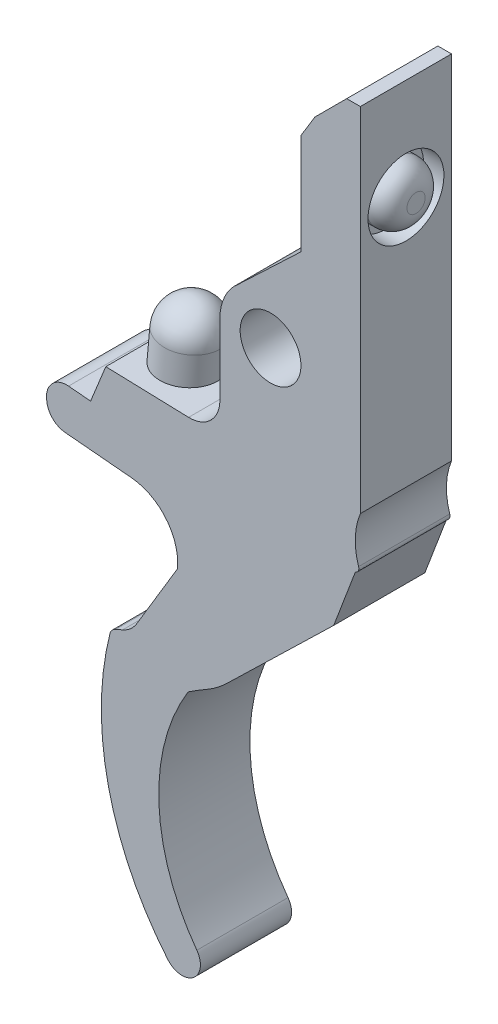
SolidWorks part; units mm, degrees
ref_plane "정면" through (0, 0, 0) normal (0, 0, 1) x (1, 0, 0)
ref_plane "윗면" through (0, 0, 0) normal (0, 1, 0) x (1, 0, 0)
ref_plane "우측면" through (0, 0, 0) normal (1, 0, 0) x (0, 0, -1)
sketch "스케치1" plane through (0, 0, 0) normal (0, 0, 1) x (1, 0, 0)
  line L0 (7.5189, 25.0781) -> (8.8664, 25.0781)
  line L1 (7.5189, 25.0781) -> (4.3842, 21.9434)
  line L2 (8.8664, 25.0781) -> (8.8664, -9.7282)
  line L3 (-5, 0) -> (-5, -10.0714)
  line L4 (-17.7666, -13.4266) -> (-19.9405, -13.2288)
  line L5 (2.9878, 19.65) -> (2.9878, 17.6612)
  line L6 (-20.2877, -17.3633) -> (-13.717, -17.9611)
  line L7 (2.9878, 17.6612) -> (2.9878, 9.7088)
  line L8 (2.9878, 9.7088) -> (-3.1847, 3.8546)
  line L9 (8.3701, -14.9782) -> (6.2381, -20.6005)
  line L10 (2.2148, 21.9434) -> (17.8049, 21.9434) construction
  line L11 (4.3842, 21.9434) -> (2.9878, 19.65)
  line L12 (6.2381, -20.6005) -> (-4.3386, -30.8592)
  line L13 (-5, -10.0714) -> (-16.2648, -9.7282)
  line L14 (-16.2648, -9.7282) -> (-17.7666, -13.4266)
  line L16 (-9.201, -23.497) -> (-13.2181, -30.1935)
  line L18 (-15.296, -31.7023) -> (-14.6082, -31.4073)
  circle A0 centre (0, 0) radius 3
  circle A1 centre (0, 0) radius 5
  arc A2 (-6.3376, -32.3623) -> (-4.3386, -30.8592) centre (-11.3009, -23.681) ccw
  arc A3 (-6.3376, -32.3623) -> (-8.1336, -33.4719) centre (9.0543, -59.2837) ccw
  arc A4 (-15.296, -31.7023) -> (-15.8352, -32.2622) centre (-14.9019, -32.6214) ccw
  arc A5 (-22.1027, -15.4958) -> (-20.2877, -17.3633) centre (-20.1065, -15.3716) ccw
  arc A6 (-19.9405, -13.2288) -> (-22.1027, -15.4958) centre (-20.1217, -15.2206) ccw
  arc A7 (8.8664, -9.7282) -> (8.6919, -14.3466) centre (15.0215, -12.2733) ccw
  arc A8 (8.6919, -14.3466) -> (8.3701, -14.9782) centre (8.2168, -14.5023) cw
  arc A9 (-13.717, -17.9611) -> (-9.201, -23.497) centre (-14.17, -22.9405) cw
  arc A11 (-14.6515, -60.0853) -> (-14.6251, -60.1395) centre (16.7757, -44.8116) ccw
  arc A13 (-8.1336, -33.4719) -> (-7.2761, -55.1306) centre (8.3107, -43.6672) ccw
  arc A14 (-15.8352, -32.2622) -> (-10.1333, -57.3697) centre (11.6079, -39.2311) ccw
  arc A15 (-10.1333, -57.3697) -> (-7.2761, -55.1306) centre (-8.7389, -56.2065) ccw
  arc A16 (-14.6082, -31.4073) -> (-13.2181, -30.1935) centre (-15.7907, -28.6502) ccw
  dimension "D1" = 6
  dimension "D2" = 10
  dimension "D4" = 2
  dimension "D5" = 0.5
  dimension "D6" = 5
  dimension "D7" = 10
  dimension "D8" = 3
  dimension "D9" = 1
  dimension "D3" = 45
extrude "보스-돌출1" add sketch "스케치1" along normal blind 9
sketch "스케치2" plane through (8.8664, 0, 0) normal (1, 0, 0) x (0, 0, -1)
  line L0 (-9, 25.0781) -> (0, 25.0781) construction
  circle A0 centre (-4.5, 15.0781) radius 3.75
  dimension "D1" = 7.5
  dimension "D2" = 10
extrude "컷-돌출1" cut sketch "스케치2" against normal blind 2
sketch "스케치3" plane through (6.8664, 0, 0) normal (1, 0, 0) x (0, 0, -1)
  circle A0 centre (-4.5, 15.0781) radius 2.9
  dimension "D1" = 5.8
extrude "보스-돌출2" add sketch "스케치3" along normal blind 3
fillet "필렛1" radius 2 1 edges at (9.8664, 17.9781, 4.5)
sketch "스케치4" plane through (-1.3573, -14.9194, 0) normal (0.0906, 0.9959, 0) x (0.9959, -0.0906, 0)
  line L0 (-3.6578, -9) -> (-3.6578, 0) construction
  circle A0 centre (-11.6578, -4.5) radius 2.9
  point P2 (-3.6578, -4.5)
  dimension "D1" = 5.8
  dimension "D2" = 8
extrude "보스-돌출3" add sketch "스케치4" along normal blind 10
fillet "필렛2" radius 2.9 1 edges at (-14.9492, -3.6416, 4.5)
fillet "필렛3" radius 3 1 edges at (-5, -10.0714, 4.5)
